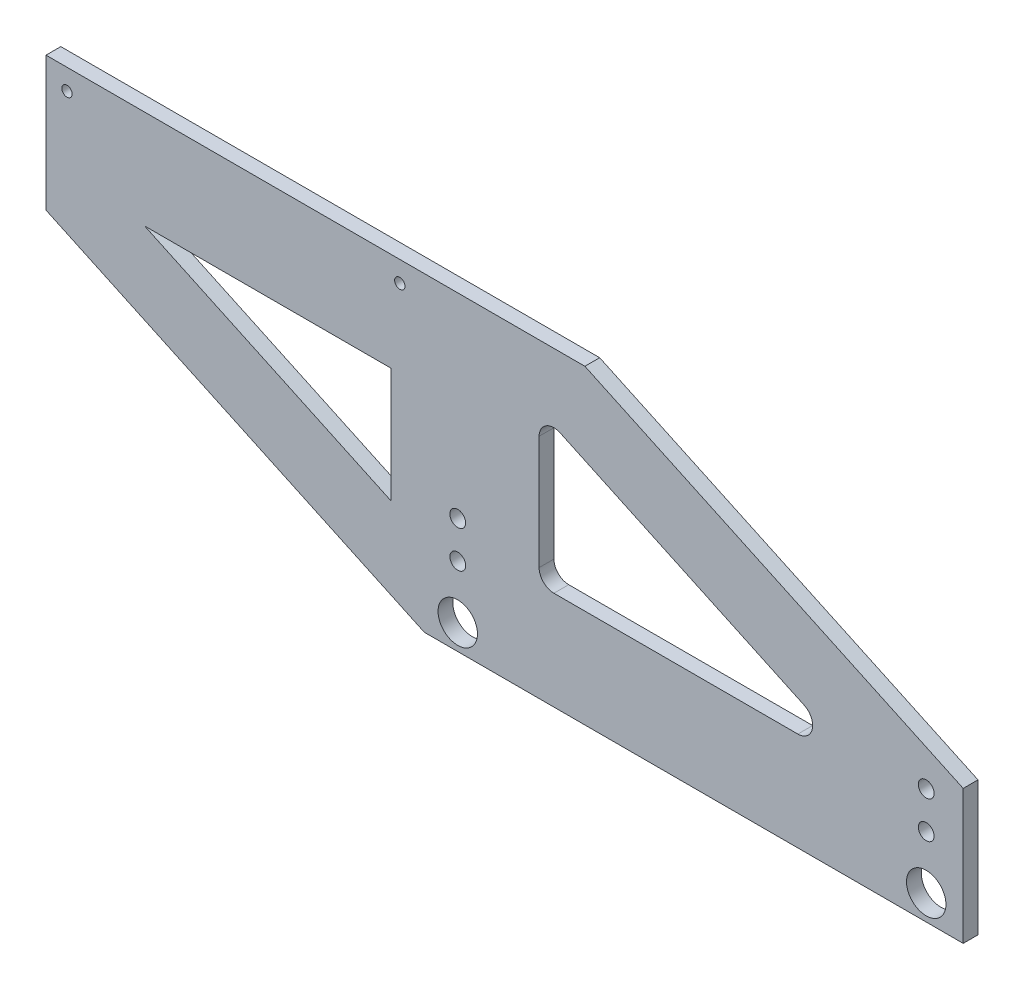
SolidWorks part; units mm, degrees
ref_plane "Front Plane" through (0, 0, 0) normal (0, 0, 1) x (1, 0, 0)
ref_plane "Top Plane" through (0, 0, 0) normal (0, 1, 0) x (1, 0, 0)
ref_plane "Right Plane" through (0, 0, 0) normal (1, 0, 0) x (0, 0, -1)
sketch "Sketch1" plane through (0, 0, 0) normal (0, 0, 1) x (1, 0, 0)
  line L0 (102.5, 14.1154) -> (102.5, 28.65) construction
  line L1 (-83.5, 74.1154) -> (25.7792, 74.1154)
  line L2 (-83.5, 74.1154) -> (-83.5, 46.8909)
  line L3 (-6.7792, 11.1154) -> (102.5, 11.1154)
  line L4 (102.5, 38.3399) -> (102.5, 11.1154)
  line L6 (-16.5, 11.1154) -> (-23.5, 11.1154) construction
  line L7 (-83.5, 71.1154) -> (-83.5, 14.1154) construction
  line L8 (-80.5, 74.1154) -> (-10.5, 74.1154) construction
  line L9 (25.7792, 74.1154) -> (102.5, 38.3399)
  line L10 (-83.5, 46.8909) -> (-6.7792, 11.1154)
  line L11 (-63.5, 54.1154) -> (-13.5, 54.1154)
  line L12 (-13.5, 54.1154) -> (-13.5, 30.8)
  line L13 (-13.5, 30.8) -> (-63.5, 54.1154)
  line L14 (16.5, 61.8917) -> (16.5, 31.1154)
  line L15 (16.5, 31.1154) -> (82.5, 31.1154)
  line L16 (82.5, 31.1154) -> (16.5, 61.8917)
  circle A0 centre (-79.25, 69.9154) radius 1.05
  circle A1 centre (-11.75, 69.9154) radius 1.05
  circle A2 centre (0, 16.2019) radius 4
  circle A3 centre (95, 16.2019) radius 4
  circle A4 centre (95, 27) radius 1.6
  circle A5 centre (95, 34.5) radius 1.6
  circle A6 centre (0, 34.5) radius 1.6
  circle A7 centre (0, 27) radius 1.6
  dimension "D1" = 3.2
  dimension "D2" = 8
  dimension "D3" = 2.1
  dimension "D4" = 115
  dimension "D5" = 15
  dimension "D6" = 15
  dimension "D7" = 20
  dimension "D8" = 20
  dimension "D9" = 50
  dimension "D10" = 20
  dimension "D11" = 30
extrude "Extrude1" add sketch "Sketch1" along normal blind 3
fillet "Fillet1" radius 3 3 edges at (82.5, 31.1154, 1.5) (16.5, 31.1154, 1.5) (16.5, 61.8917, 1.5)
